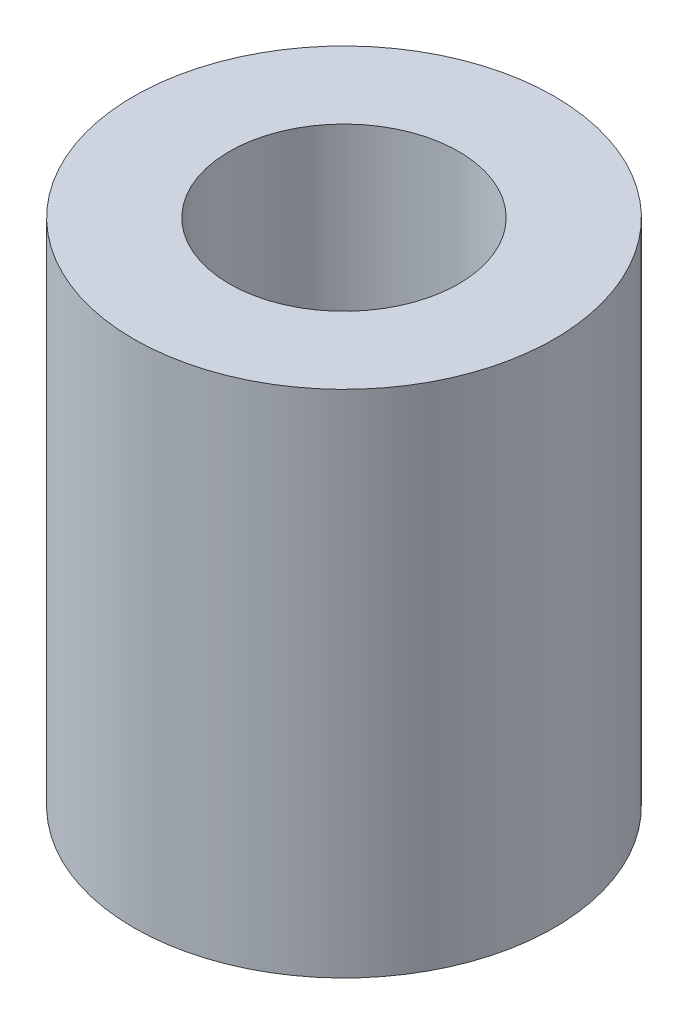
SolidWorks part; units mm, degrees
ref_plane "Front Plane" through (0, 0, 0) normal (0, 0, 1) x (1, 0, 0)
ref_plane "Top Plane" through (0, 0, 0) normal (0, 1, 0) x (1, 0, 0)
ref_plane "Right Plane" through (0, 0, 0) normal (1, 0, 0) x (0, 0, -1)
sketch "Sketch1" plane through (0, 0, 0) normal (0, 1, 0) x (1, 0, 0)
  circle A0 centre (0, 0) radius 1.8
  circle A1 centre (0, 0) radius 3.3
  dimension "D1" = 3.6
  dimension "D2" = 1.5
extrude "Boss-Extrude1" add sketch "Sketch1" along normal blind 8
